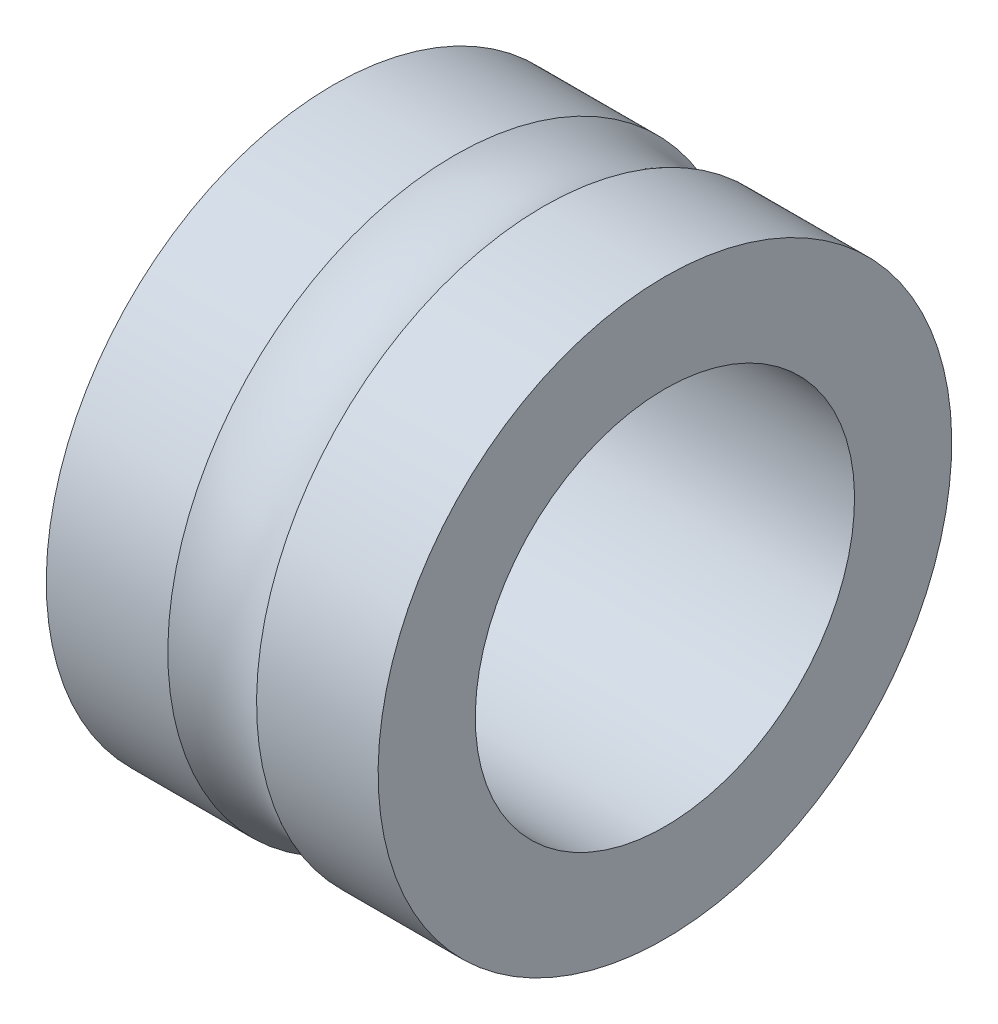
SolidWorks part; units mm, degrees
ref_plane "Front Plane" through (0, 0, 0) normal (0, 0, 1) x (1, 0, 0)
ref_plane "Top Plane" through (0, 0, 0) normal (0, 1, 0) x (1, 0, 0)
ref_plane "Right Plane" through (0, 0, 0) normal (1, 0, 0) x (0, 0, -1)
sketch "Sketch2" plane through (0, 0, 0) normal (0, 0, 1) x (1, 0, 0)
  line L0 (23.6602, 0) -> (-21.7547, 0) construction
  line L1 (3.5, 11) -> (-3.5, 11)
  line L2 (3.5, 11) -> (3.5, 9.6)
  line L3 (3.5, 9.6) -> (-3.5, 9.6)
  line L4 (-3.5, 9.6) -> (-3.5, 11)
  line L5 (3.5, 6.05) -> (3.5, 4)
  line L6 (3.5, 4) -> (-3.5, 4)
  line L7 (-3.5, 4) -> (-3.5, 6.05)
  line L8 (-3.5, 6.05) -> (3.5, 6.05)
  circle A0 centre (0, 7.8) radius 1.9845
  point P9 (0, 11)
  dimension "Ball Bearing Size" = 3.969
  dimension "Bearing Width" = 7
  dimension "Inner Casing Inner" = 4
  dimension "Inner Casing Outter" = 6.05
  dimension "Outter Casing Inner" = 9.6
  dimension "Outter Case Outter" = 11
  dimension "D1" = 1.75
revolve "Revolve1" add sketch "Sketch2" angle 360 about L0
sketch "Sketch3" plane through (0, 0, 0) normal (1, 0, 0) x (0, 0, -1)
  circle A0 centre (0, 0) radius 7.8
  dimension "Ball Track" = 15.6
sketch "Sketch4" plane through (0, 0, 0) normal (0, 0, 1) x (1, 0, 0)
  line L0 (-6.5669, 0) -> (7.975, 0) construction
equation "\"Motor Width\"= 42.3'eg: For stepper motor Nema 17 = 42.3mm"
equation "\"Motor Hole Config Width\"= 31'eg: For stepper motor Nema 17 = 31"
equation "\"Mounting Hole Diameter\"= 3'eg: For Nema 17 3mm"
equation "\"Motor Depth\"= 50'eg: For Nema 17 50mm"
equation "\"Exposed Shaft Length\"= 22'eg: For Nema 17 22mm"
equation "\"Shaft Seround Depthr\"= 2'eg: For Nema 17 2mm"
equation "\"Shaft Diameter\"= 5'eg: For Nema 17 5mm"
equation "\"Top/Bottom Casing Depth\"= 10'Guess"
equation "\"Mid Casing Depth\"= \"Motor Depth\" - 2 * ( \"Top/Bottom Casing Depth\" )"
equation "\"Bearing Outter Diameter\"= 22' From Spec 608z = 22mm"
equation "\"Shaft Clearance Hole\"= \"Shaft Diameter\"+1.5'Guess"
equation "\"Bearing Ball Size\"= 3.969'From Spec"
equation "\"Bearing Inner Case Inner Diameter\"= 8'From Spec"
equation "\"Bearing Inner Case Outter Diameter\"= 12.1'From Spec"
equation "\"Bearing Outter Case Inner Diameter\"= 19.2'From Spec"
equation "\"Bearing Width\"= 7'From Spec"
equation "\"Bearing Width@Sketch2\"=\"Bearing Width\""
equation "\"Inner Casing Inner@Sketch2\"=\"Bearing Inner Case Inner Diameter\"/2"
equation "\"Inner Casing Outter@Sketch2\"=\"Bearing Inner Case Outter Diameter\"/2"
equation "\"Outter Casing Inner@Sketch2\"=\"Bearing Outter Case Inner Diameter\"/2"
equation "\"Outter Case Outter@Sketch2\"=\"Bearing Outter Diameter\"/2"
equation "\"Ball Bearing Size@Sketch2\"=\"Bearing Ball Size\""
equation "\"Ball Track@Sketch3\"=\"Bearing Inner Case Outter Diameter\"+2*(1.75)"
